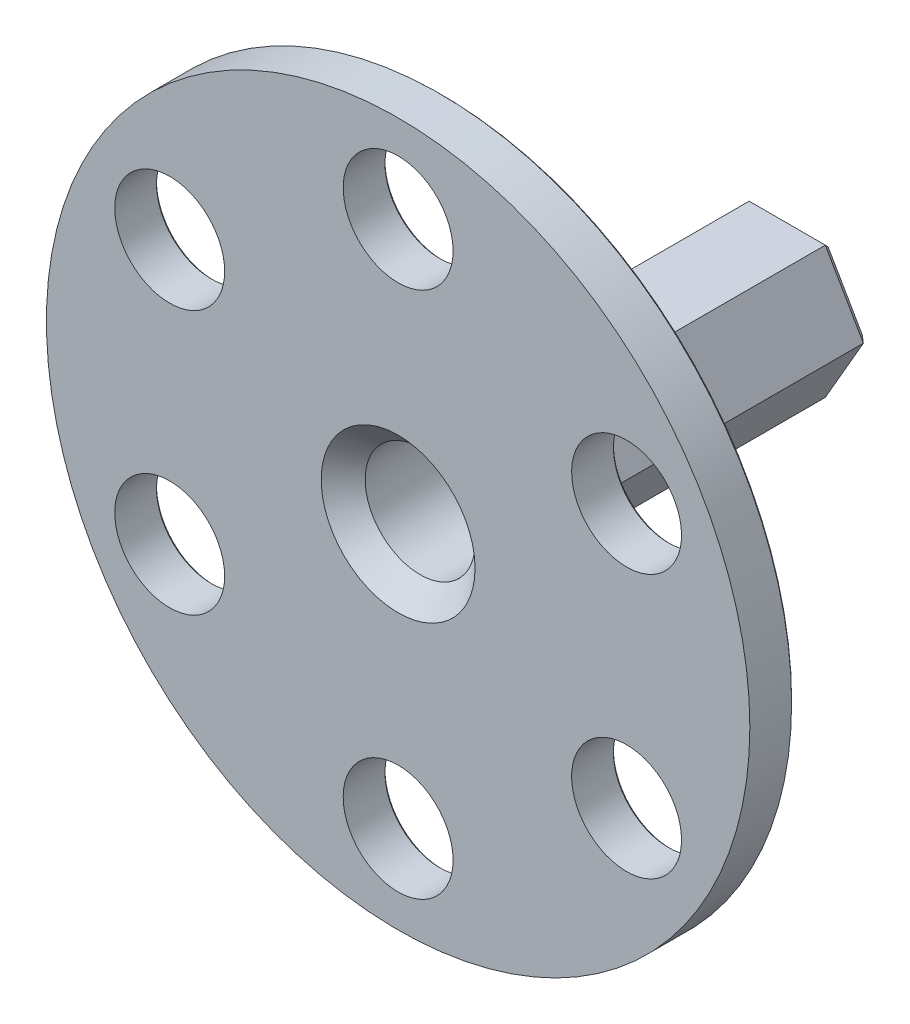
SolidWorks part; units mm, degrees
ref_plane "Front Plane" through (0, 0, 0) normal (0, 0, 1) x (1, 0, 0)
ref_plane "Top Plane" through (0, 0, 0) normal (0, 1, 0) x (1, 0, 0)
ref_plane "Right Plane" through (0, 0, 0) normal (1, 0, 0) x (0, 0, -1)
sketch "Sketch1" plane through (0, 0, 0) normal (0, 0, 1) x (1, 0, 0)
  circle A0 centre (0, 0) radius 32
  dimension "D1" = 64
extrude "Boss-Extrude1" add sketch "Sketch1" against normal blind 4
sketch "Sketch2" plane through (0, 0, 0) normal (0, 0, 1) x (1, 0, 0)
  circle A0 centre (0, 0) radius 24 construction
  circle A1 centre (0, 24) radius 5
  dimension "D1" = 10
  dimension "D2" = 48
extrude "Cut-Extrude1" cut sketch "Sketch2" against normal through all
pattern_circular "CirPattern1" count 6 over 360 about axis through (0, 0, 0) along (0, 0, 1) of "Cut-Extrude1"
sketch "Sketch3" plane through (0, 0, -4) normal (0, 0, -1) x (-1, 0, 0)
  line L1 (-3.4641, 6) -> (-6.9282, 0)
  line L2 (-6.9282, 0) -> (-3.4641, -6)
  line L3 (-3.4641, -6) -> (3.4641, -6)
  line L4 (3.4641, -6) -> (6.9282, 0)
  line L5 (6.9282, 0) -> (3.4641, 6)
  line L6 (3.4641, 6) -> (-3.4641, 6)
  circle A0 centre (0, 0) radius 6 construction
  dimension "D1" = 12
extrude "Boss-Extrude2" add sketch "Sketch3" along normal blind 32
chamfer "Chamfer1" distance 2 angle 45 6 edges at (5.1962, 3, -4) (5.1962, -3, -4) (0, -6, -4) (-5.1962, -3, -4) (-5.1962, 3, -4) (0, 6, -4)
chamfer "Chamfer2" distance 0.2 angle 45 7 edges at (-5, -24, -4) (18.2846, -16.3301, -4) (23.2846, 7.6699, -4) (5, 24, -4) (-18.2846, 16.3301, -4) (-23.2846, -7.6699, -4) (32, 0, -4)
sketch "Sketch4" plane through (0, 0, 0) normal (0, 0, 1) x (1, 0, 0)
  circle A0 centre (0, 0) radius 5
  dimension "D1" = 10
extrude "Cut-Extrude2" cut sketch "Sketch4" against normal blind 32
chamfer "Chamfer3" distance 0.6 angle 45 6 edges at (-5.1962, 3, -36) (-5.1962, -3, -36) (0, -6, -36) (5.1962, -3, -36) (5.1962, 3, -36) (0, 6, -36)
chamfer "Chamfer4" distance 5 angle 45 1 edges at (5, 0, -32)
chamfer "Chamfer5" distance 2 angle 45 1 edges at (5, 0, 0)
scale "Scale1" scale about centroid uniform scaling yes scale factor 0.4
